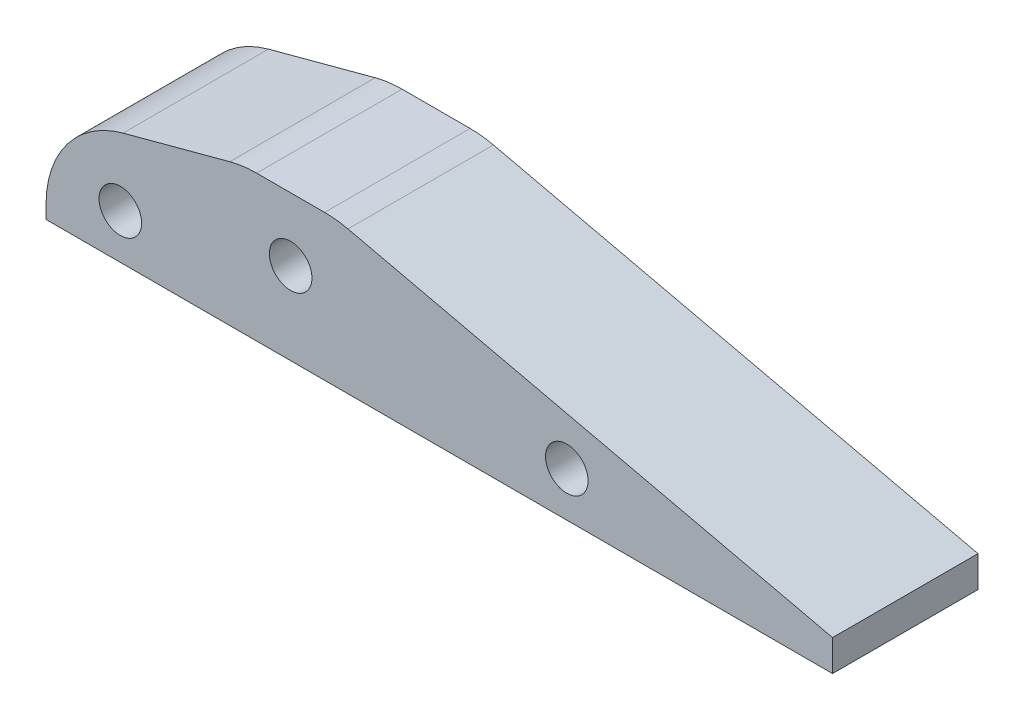
SolidWorks part; units mm, degrees
material "ABS"
ref_plane "Front Plane" through (0, 0, 0) normal (0, 0, 1) x (1, 0, 0)
ref_plane "Top Plane" through (0, 0, 0) normal (0, 1, 0) x (1, 0, 0)
ref_plane "Right Plane" through (0, 0, 0) normal (1, 0, 0) x (0, 0, -1)
sketch "Sketch1" plane through (0, 0, 0) normal (0, 0, 1) x (1, 0, 0)
  line L0 (0, 0) -> (0, 8.92)
  line L1 (0, 8.92) -> (18.9588, 14)
  line L2 (18.9588, 14) -> (27.9588, 14)
  line L3 (27.9588, 14) -> (75.7082, 3)
  line L4 (75.7082, 3) -> (75.7082, 0)
  line L5 (75.7082, 0) -> (0, 0)
  line L6 (0, 0) -> (0, 23.7543) construction
  dimension "D1" = 8.92
  dimension "D2" = 75
  dimension "D3" = 9
  dimension "D4" = 14
  dimension "D5" = 49
  dimension "D6" = 3
extrude "Boss-Extrude1" add sketch "Sketch1" along normal blind 14
fillet "Fillet1" radius 10 1 edges at (0, 8.92, 7)
fillet "Fillet2" radius 10 2 edges at (27.9588, 14, 7) (18.9588, 14, 7)
sketch "Sketch2" plane through (0, 0, 0) normal (0, 0, -1) x (-1, 0, 0)
  line L1 (-52.1792, 7.8436) -> (-54.2288, 4.2936)
  line L2 (-54.2288, 4.2936) -> (-52.1792, 0.7436)
  line L3 (-52.1792, 0.7436) -> (-48.0801, 0.7436)
  line L4 (-48.0801, 0.7436) -> (-46.0305, 4.2936)
  line L5 (-46.0305, 4.2936) -> (-48.0801, 7.8436)
  line L6 (-48.0801, 7.8436) -> (-52.1792, 7.8436)
  line L7 (-25.5982, 11.4569) -> (-27.6478, 7.9069)
  line L8 (-27.6478, 7.9069) -> (-25.5982, 4.3569)
  line L9 (-25.5982, 4.3569) -> (-21.499, 4.3569)
  line L10 (-21.499, 4.3569) -> (-19.4494, 7.9069)
  line L11 (-19.4494, 7.9069) -> (-21.499, 11.4569)
  line L12 (-21.499, 11.4569) -> (-25.5982, 11.4569)
  line L13 (-9.2046, 7.8436) -> (-11.2542, 4.2936)
  line L14 (-11.2542, 4.2936) -> (-9.2046, 0.7436)
  line L15 (-9.2046, 0.7436) -> (-5.1054, 0.7436)
  line L16 (-5.1054, 0.7436) -> (-3.0558, 4.2936)
  line L17 (-3.0558, 4.2936) -> (-5.1054, 7.8436)
  line L18 (-5.1054, 7.8436) -> (-9.2046, 7.8436)
  circle A0 centre (-50.1296, 4.2936) radius 3.55 construction
  circle A1 centre (-23.5486, 7.9069) radius 3.55 construction
  circle A2 centre (-7.155, 4.2936) radius 3.55 construction
extrude "Cut-Extrude1" cut sketch "Sketch2" against normal blind 5
sketch "Sketch3" plane through (0, 0, 5) normal (0, 0, -1) x (-1, 0, 0)
  circle A0 centre (-50.1296, 4.2936) radius 2.05
  circle A1 centre (-23.5486, 7.9069) radius 2.05
  circle A2 centre (-7.155, 4.2936) radius 2.05
  dimension "D1" = 4.1
extrude "Cut-Extrude2" cut sketch "Sketch3" against normal through all
